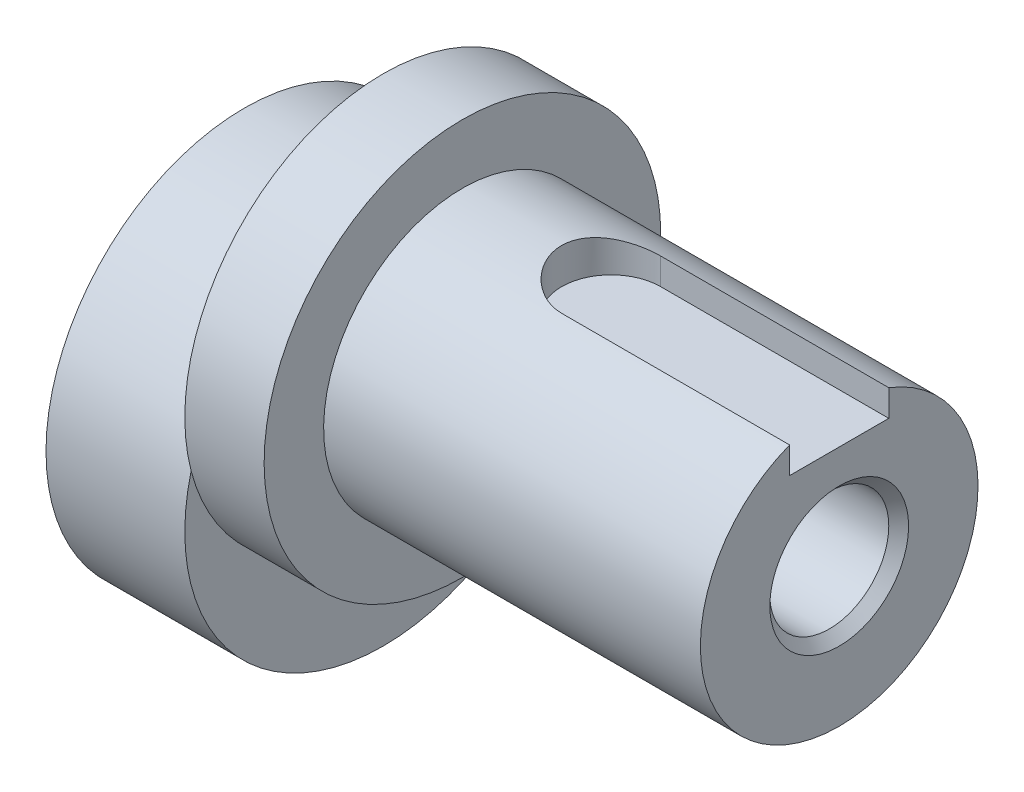
SolidWorks part; units mm, degrees
ref_plane "Front Plane" through (0, 0, 0) normal (0, 0, 1) x (1, 0, 0)
ref_plane "Top Plane" through (0, 0, 0) normal (0, 1, 0) x (1, 0, 0)
ref_plane "Right Plane" through (0, 0, 0) normal (1, 0, 0) x (0, 0, -1)
sketch "Sketch1" plane through (0, 0, 0) normal (1, 0, 0) x (0, 0, -1)
  circle A0 centre (0, 0) radius 10
  dimension "D1" = 20
extrude "Boss-Extrude1" add sketch "Sketch1" along normal blind 7
sketch "Sketch2" plane through (7, 0, 0) normal (1, 0, 0) x (0, 0, -1)
  circle A0 centre (0, 5) radius 10
  dimension "D1" = 20
  dimension "D2" = 5
extrude "Boss-Extrude2" add sketch "Sketch2" along normal blind 4
sketch "Sketch3" plane through (11, 0, 0) normal (1, 0, 0) x (0, 0, -1)
  circle A0 centre (0, 5) radius 7
  dimension "D1" = 14
extrude "Boss-Extrude3" add sketch "Sketch3" along normal blind 19
sketch "Sketch4" plane through (30, 0, 0) normal (1, 0, 0) x (0, 0, -1)
  circle A0 centre (0, 5) radius 3
  dimension "D1" = 6
extrude "Cut-Extrude1" cut sketch "Sketch4" against normal through all both and the other way through all
chamfer "Chamfer1" distance 0.5 angle 45 2 edges at (30, 5, -3) (0, 5, -3)
sketch "Sketch5" plane through (0, 0, 0) normal (0, 1, 0) x (1, 0, 0)
  line L0 (-3.8994, 0) -> (41.4253, 0) construction
  line L1 (16, 0) -> (16, 5.6268) construction
  line L2 (32.7908, 2.5) -> (18.5, 2.5)
  line L3 (32.7908, 2.5) -> (32.7908, -2.5)
  line L4 (32.7908, -2.5) -> (18.5, -2.5)
  line L5 (30, -7) -> (30, 7) construction
  arc A0 (18.5, 2.5) -> (18.5, -2.5) centre (18.5, 0) ccw
  dimension "D1" = 2.5
  dimension "D2" = 14
extrude "Cut-Extrude2" cut sketch "Sketch5" along normal blind 19 from offset 10.2
